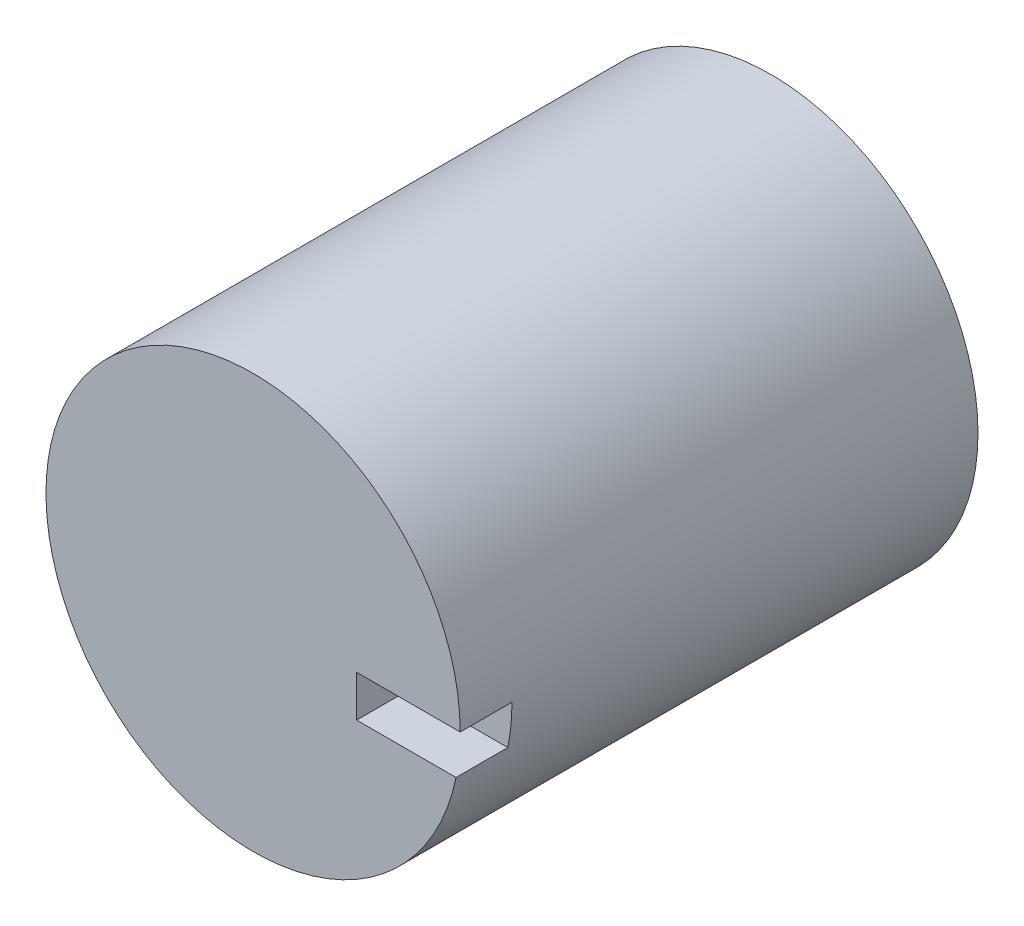
SolidWorks part; units mm, degrees
ref_plane "前视基准面" through (0, 0, 0) normal (0, 0, 1) x (1, 0, 0)
ref_plane "上视基准面" through (0, 0, 0) normal (0, 1, 0) x (1, 0, 0)
ref_plane "右视基准面" through (0, 0, 0) normal (1, 0, 0) x (0, 0, -1)
other "Configuration Table"
sketch "草图1" plane through (0, 0, 0) normal (0, 0, 1) x (1, 0, 0)
  circle A0 centre (0, 0) radius 20
  dimension "D1" = 40
extrude "凸台-拉伸1" add sketch "草图1" against normal blind 50
sketch "草图2" plane through (0, 0, 0) normal (0, 1, 0) x (1, 0, 0)
  line L1 (10, -5) -> (40, -5)
  line L2 (10, -5) -> (10, 5)
  line L3 (10, 5) -> (40, 5)
  line L4 (40, -5) -> (40, 5)
extrude "切除-拉伸1" cut sketch "草图2" against normal blind 4
